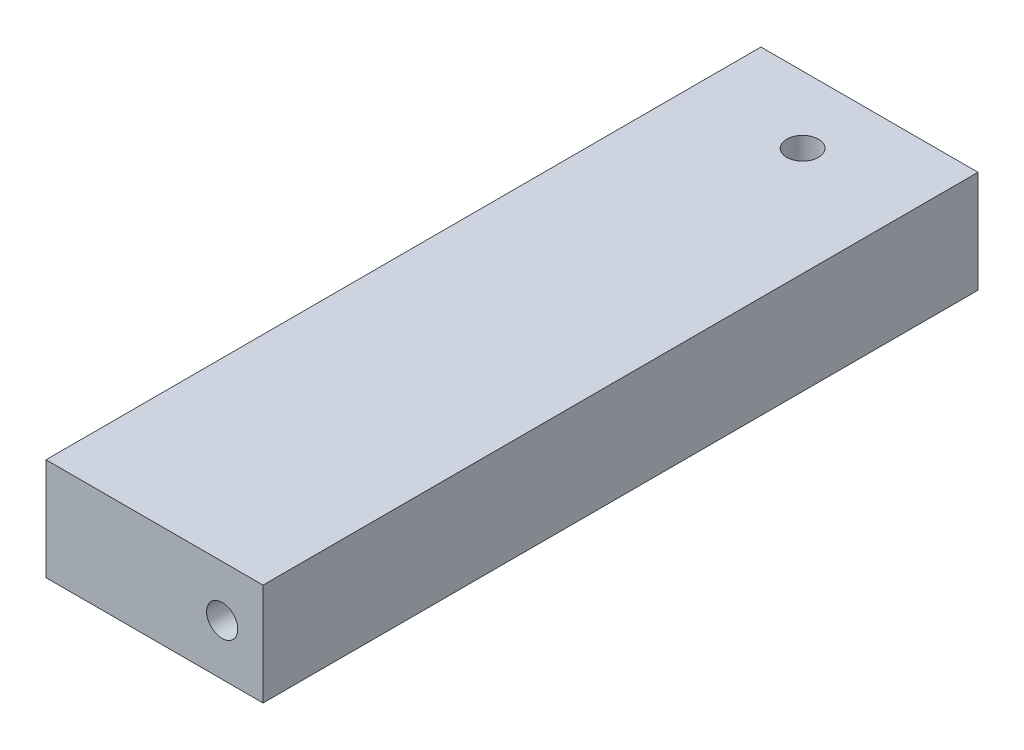
SolidWorks part; units mm, degrees
ref_plane "Front Plane" through (0, 0, 0) normal (0, 0, 1) x (1, 0, 0)
ref_plane "Top Plane" through (0, 0, 0) normal (0, 1, 0) x (1, 0, 0)
ref_plane "Right Plane" through (0, 0, 0) normal (1, 0, 0) x (0, 0, -1)
sketch "Sketch1" plane through (0, 0, 0) normal (0, 1, 0) x (1, 0, 0)
  line L1 (-2.1455, 1.119) -> (2.1045, 1.119)
  line L2 (-2.1455, 1.119) -> (-2.1455, -12.881)
  line L3 (-2.1455, -12.881) -> (2.1045, -12.881)
  line L4 (2.1045, 1.119) -> (2.1045, -12.881)
  dimension "D1" = 4.25
  dimension "D2" = 14
extrude "Boss-Extrude1" add sketch "Sketch1" along normal blind 2
scale "Scale1" scale about centroid uniform scaling yes scale factor 10
sketch "Sketch2" plane through (0, 0, -64.119) normal (0, 0, -1) x (-1, 0, 0)
  circle A0 centre (-13.2295, 1) radius 3.05
extrude "Cut-Extrude1" cut sketch "Sketch2" against normal through all
sketch "Sketch4" plane through (0, 11, 0) normal (0, 1, 0) x (1, 0, 0)
  circle A0 centre (-0.0205, 51.019) radius 3.1
extrude "Cut-Extrude2" cut sketch "Sketch4" against normal through all
